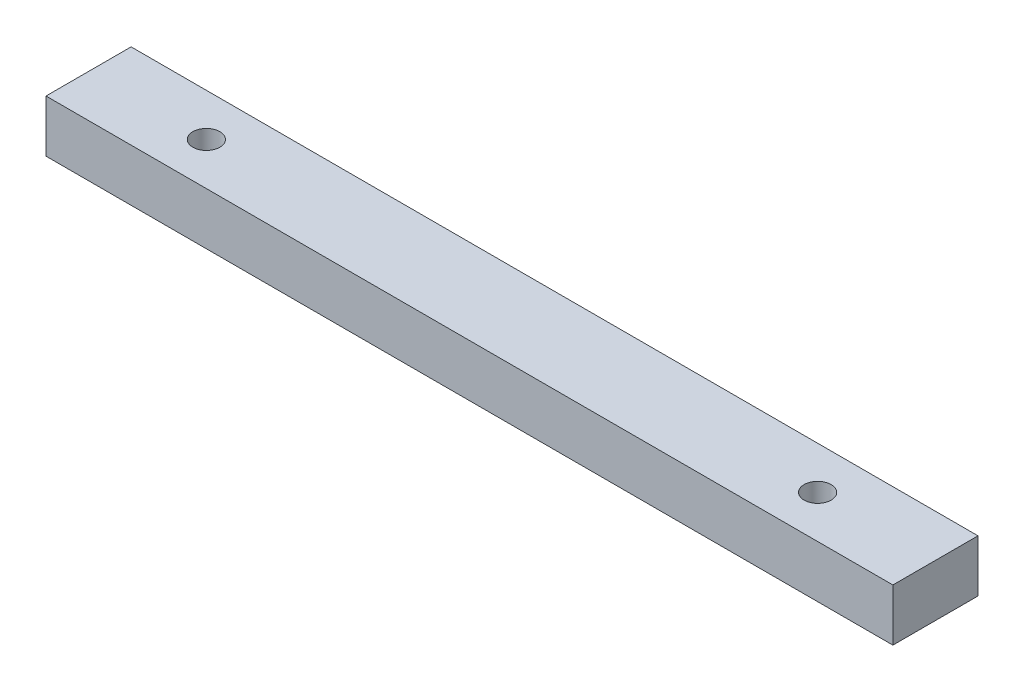
SolidWorks part; units mm, degrees
ref_plane "Front Plane" through (0, 0, 0) normal (0, 0, 1) x (1, 0, 0)
ref_plane "Top Plane" through (0, 0, 0) normal (0, 1, 0) x (1, 0, 0)
ref_plane "Right Plane" through (0, 0, 0) normal (1, 0, 0) x (0, 0, -1)
sketch "Sketch1" plane through (0, 0, 0) normal (0, 0, 1) x (1, 0, 0)
  line L1 (-7.3932, 14.7324) -> (390.6068, 14.7324)
  line L2 (-7.3932, 14.7324) -> (-7.3932, -9.7676)
  line L3 (-7.3932, -9.7676) -> (390.6068, -9.7676)
  line L4 (390.6068, 14.7324) -> (390.6068, -9.7676)
  dimension "D1" = 24.5
  dimension "D2" = 398
extrude "Boss-Extrude1" add sketch "Sketch1" along normal blind 40
sketch "Sketch4" plane through (0, 14.7324, 0) normal (0, 1, 0) x (1, 0, 0)
  circle A2 centre (335.2348, -20) radius 6.35
  circle A3 centre (47.9788, -20) radius 6.35
  point P6 (0, 0)
  point P12 (334.9013, -20)
  dimension "D2" = 12.7
  dimension "D4" = 12.7
extrude "Cut-Extrude1" cut sketch "Sketch4" against normal blind 40
equation "\"diameter\"= 12.7mm"
equation "\"length\"= 350mm"
equation "\"b\"= 40mm"
equation "\"h\"= 24.5mm"
